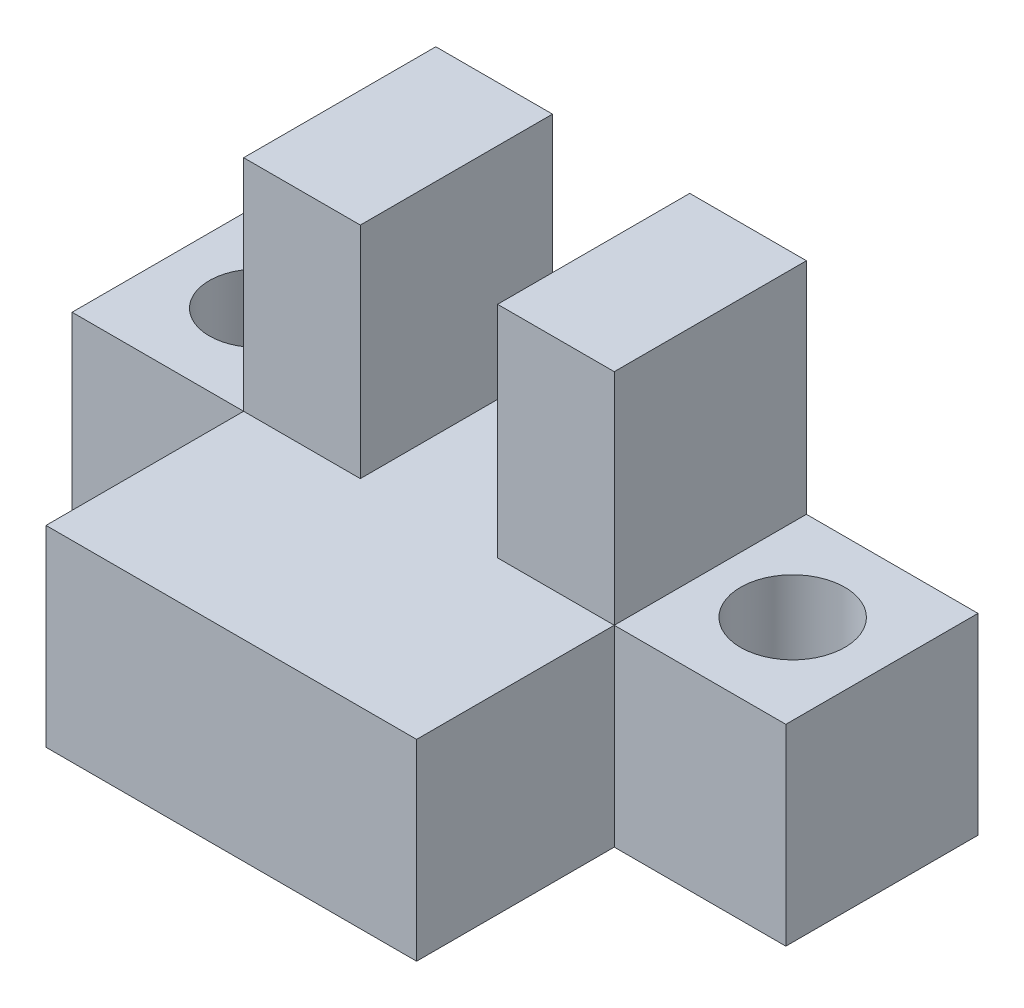
SolidWorks part; units mm, degrees
ref_plane "Front Plane" through (0, 0, 0) normal (0, 0, 1) x (1, 0, 0)
ref_plane "Top Plane" through (0, 0, 0) normal (0, 1, 0) x (1, 0, 0)
ref_plane "Right Plane" through (0, 0, 0) normal (1, 0, 0) x (0, 0, -1)
sketch "Sketch1" plane through (0, 0, 0) normal (0, 1, 0) x (1, 0, 0)
  line L0 (13, 14.2) -> (13, 0) construction
  line L1 (6.25, 0) -> (19.75, 0)
  line L2 (0, 7.2) -> (0, 14.2)
  line L3 (0, 14.2) -> (26, 14.2)
  line L4 (26, 7.2) -> (26, 14.2)
  line L5 (0, 7.2) -> (6.25, 7.2)
  line L6 (6.25, 0) -> (6.25, 7.2)
  line L7 (19.75, 0) -> (19.75, 7.2)
  line L8 (19.75, 7.2) -> (26, 7.2)
  point P4 (31.6218, -73.5662)
  point P14 (-52.3717, 28.1973)
  point P16 (13.5982, 28.7692)
  dimension "D1" = 26
  dimension "D3" = 7.2
  dimension "D4" = 6.25
  dimension "D5" = 6.25
extrude "Boss-Extrude1" add sketch "Sketch1" along normal blind 7
sketch "Sketch2" plane through (0, 7, 0) normal (0, 1, 0) x (1, 0, 0)
  line L0 (26, 14.2) -> (0, 14.2) construction
  line L1 (6.25, 14.2) -> (10.5, 14.2)
  line L2 (6.25, 14.2) -> (6.25, 7.2)
  line L3 (6.25, 7.2) -> (10.5, 7.2)
  line L4 (10.5, 14.2) -> (10.5, 7.2)
  line L5 (19.75, 7.2) -> (26, 7.2) construction
  line L6 (15.5, 14.2) -> (19.75, 14.2)
  line L7 (15.5, 14.2) -> (15.5, 7.2)
  line L8 (15.5, 7.2) -> (19.75, 7.2)
  line L9 (19.75, 14.2) -> (19.75, 7.2)
  line L10 (26, 7.2) -> (26, 14.2) construction
  line L11 (0, 14.2) -> (0, 7.2) construction
  dimension "D1" = 4.25
  dimension "D2" = 4.25
  dimension "D3" = 6.25
  dimension "D4" = 6.25
extrude "Boss-Extrude2" add sketch "Sketch2" along normal blind 8
sketch "Sketch3" plane through (0, 7, 0) normal (0, 1, 0) x (1, 0, 0)
  line L1 (26, 7.2) -> (26, 14.2) construction
  line L4 (0, 14.2) -> (0, 7.2) construction
  line L5 (26, 14.2) -> (19.75, 14.2) construction
  line L6 (6.25, 14.2) -> (0, 14.2) construction
  circle A1 centre (22.75, 10.7) radius 1.8995
  circle A2 centre (3.25, 10.7) radius 1.75
  dimension "D1" = 3.5
  dimension "D2" = 3.25
  dimension "D3" = 3.5
  dimension "D4" = 3.5
  dimension "D5" = 3.25
extrude "Cut-Extrude1" cut sketch "Sketch3" against normal blind 19
